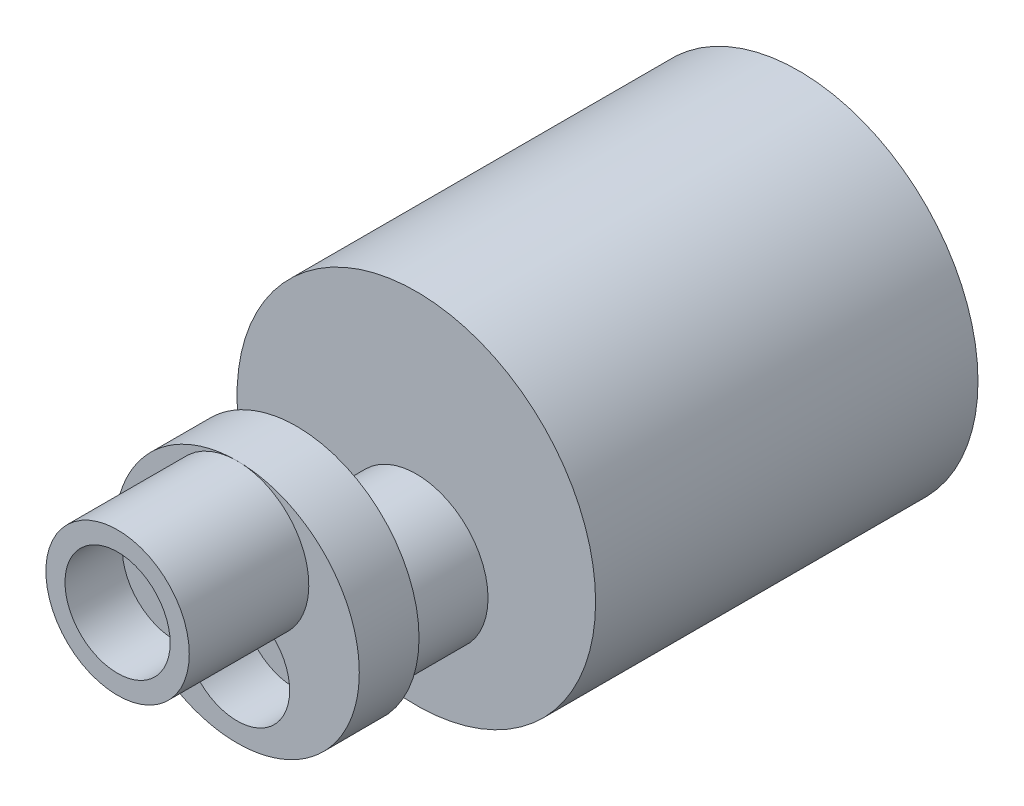
SolidWorks part; units mm, degrees
ref_plane "Front Plane" through (0, 0, 0) normal (0, 0, 1) x (1, 0, 0)
ref_plane "Top Plane" through (0, 0, 0) normal (0, 1, 0) x (1, 0, 0)
ref_plane "Right Plane" through (0, 0, 0) normal (1, 0, 0) x (0, 0, -1)
sketch "Sketch1" plane through (0, 0, 0) normal (0, 0, 1) x (1, 0, 0)
  circle A0 centre (0, 0) radius 7.5
  dimension "D1" = 15
extrude "Boss-Extrude1" add sketch "Sketch1" along normal blind 16
sketch "Sketch2" plane through (0, 0, 16) normal (0, 0, 1) x (1, 0, 0)
  circle A0 centre (0, -2.1125) radius 3
  dimension "D2" = 6
  dimension "D1" = 2.1125
extrude "Boss-Extrude2" add sketch "Sketch2" along normal blind 5
sketch "Sketch3" plane through (0, 0, 21) normal (0, 0, 1) x (1, 0, 0)
  circle A0 centre (0, 0) radius 5.1125
extrude "Boss-Extrude3" add sketch "Sketch3" along normal blind 2.5 contours A0
sketch "Sketch5" plane through (0, 0, 23.5) normal (0, 0, 1) x (1, 0, 0)
  circle A0 centre (0, 2.1125) radius 3
  dimension "D1" = 6
  dimension "D2" = 2.1125
extrude "Boss-Extrude4" add sketch "Sketch5" along normal blind 5
hole_wizard "CBORE for M2 Hex Socket Head Cap Screw1" positions "Sketch6" profile "Sketch8" counterbore size "M2" standard "ISO"
sketch "Sketch6" plane through (0, 0, 28.5) normal (0, 0, 1) x (1, 0, 0)
  circle A2 centre (0, 2.1125) radius 3
  circle A3 centre (0, 2.1125) radius 3
  point P5 (0, 2.1125)
  dimension "D1" = 0
sketch "Sketch8" plane through (0, 2.1125, 28.5) normal (1, 0, 0) x (0, -1, 0)
  line L0 (0, 0) -> (0, 7.5)
  line L1 (0, 7.5) -> (1.2, 7.5)
  line L3 (1.2, 7.5) -> (1.2, 2.4)
  line L4 (1.2, 2.4) -> (2.2, 2.4)
  line L5 (2.2, 2.4) -> (2.2, 0)
  line L7 (2.2, 0) -> (0, 0)
  line L11 (0, -6.35) -> (0, 107.95) construction
  dimension "Thru Hole Dia." = 2.4
  dimension "Thru Hole Depth" = 7.5
  dimension "C'Bore Dia." = 4.4
  dimension "C'Bore Depth" = 2.4
hole_wizard "CBORE for M2 Hex Socket Head Cap Screw2" positions "Sketch12" profile "Sketch10" counterbore size "M2" standard "ISO"
sketch "Sketch12" plane through (0, 0, 23.5) normal (0, 0, 1) x (1, 0, 0)
  circle A0 centre (0, -2.1125) radius 3 construction
  circle A1 centre (0, -2.1125) radius 3
  point P0 (0, -2.1125)
sketch "Sketch10" plane through (0, -2.1125, 23.5) normal (1, 0, 0) x (0, -1, 0)
  line L0 (0, 0) -> (0, 14.721)
  line L1 (0, 14.721) -> (1.2, 14)
  line L2 (1.2, 14) -> (1.2, 2.4)
  line L3 (1.2, 2.4) -> (2.2, 2.4)
  line L4 (2.2, 2.4) -> (2.2, 0)
  line L5 (2.2, 0) -> (0, 0)
  line L10 (0, 14.721) -> (-1.2, 14) construction
  line L11 (0, -6.35) -> (0, 107.95) construction
  dimension "Hole Dia." = 2.4
  dimension "Hole Depth" = 14
  dimension "C'Bore Dia." = 4.4
  dimension "C'Bore Depth" = 2.4
  dimension "Drill Angle" = 118
equation "\"roller_radius\"= 6.5"
equation "\"eccentricity\"= \"roller_radius\" * 0.325"
equation "\"outer_radius\"= 40"
equation "\"eccentric_shaft_radius\"= 16"
equation "\"rotor_width\"= 10"
equation "\"housing_depth\"= 40"
equation "\"bottom_depth\"= 5"
equation "\"roller_bearing_OD\"= \"roller_radius\" * 2"
equation "\"roller_bearing_ID\"= 6"
equation "\"eccentric_bearing_ID\"= 6"
equation "\"eccentric_bearing_OD\"= 15"
equation "\"roller_bearing_height\"= 5"
equation "\"eccentric_bearing_height\"= 5"
equation "\"bottom_bearing_ID\"= 15"
equation "\"bottom_bearing_OD\"= 32"
equation "\"bottom_bearing_height\"= 9"
equation "\"distance_to_output_rotor_holes\"= 20"
equation "\"D1@Sketch1\"=\"bottom_bearing_ID\""
equation "\"D1@Boss-Extrude1\"=\"bottom_bearing_height\"+7"
equation "\"D1@Sketch2\"=\"eccentricity\""
equation "\"D2@Sketch2\"=\"eccentric_bearing_ID\""
equation "\"D1@Boss-Extrude2\"=\"eccentric_bearing_height\""
equation "\"D1@Sketch5\"=\"eccentric_bearing_ID\""
equation "\"D2@Sketch5\"=\"eccentricity\""
equation "\"D1@Boss-Extrude4\"=\"eccentric_bearing_height\""
equation "\"output_bearing_ID\" = 25"
equation "\"output_bearing_OD\" = 37"
equation "\"output_bearing_height\" = 7"
equation "\"number_of_rollers\" = 15"
equation "\"housing_height\" = 27"
equation "\"spacer_1\" = 7"
equation "\"spacer_2\" = 2.5"
equation "\"spacer_3\" = 7.5"
equation "\"roller_pin_depth\" = 5"
equation "\"D1@Boss-Extrude3\"=\"spacer_2\""
